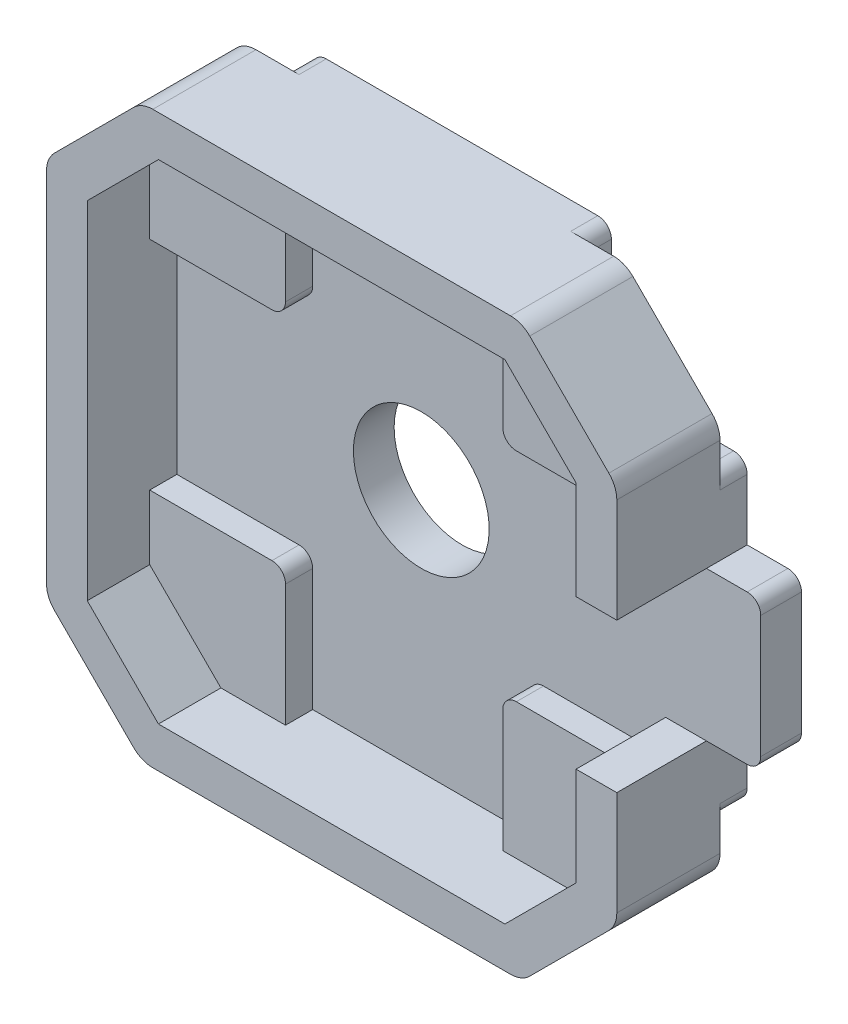
SolidWorks part; units mm, degrees
ref_plane "Front Plane" through (0, 0, 0) normal (0, 0, 1) x (1, 0, 0)
ref_plane "Top Plane" through (0, 0, 0) normal (0, 1, 0) x (1, 0, 0)
ref_plane "Right Plane" through (0, 0, 0) normal (1, 0, 0) x (0, 0, -1)
sketch "Sketch1" plane through (0, 0, 0) normal (0, 0, 1) x (1, 0, 0)
  line L1 (-21, 21) -> (21, 21)
  line L2 (-21, 21) -> (-21, -21)
  line L3 (-21, -21) -> (21, -21)
  line L4 (21, 21) -> (21, -21)
  line L5 (-21, 21) -> (21, -21) construction
  line L6 (-21, -21) -> (21, 21) construction
  point P0 (0, 0)
  dimension "D1" = 42
  dimension "D2" = 42
extrude "Boss-Extrude1" add sketch "Sketch1" along normal mid plane 9.6
sketch "Sketch2" plane through (0, 0, 4.8) normal (0, 0, 1) x (1, 0, 0)
  line L0 (0, 7.5354) -> (0, -7.4639) construction
  line L1 (-9.7138, 0) -> (7.7854, 0) construction
  line L2 (-21, 21) -> (-21, 14)
  line L3 (-21, 21) -> (-21, -21) construction
  line L4 (-21, 14) -> (-14, 21)
  line L5 (21, 21) -> (-21, 21) construction
  line L6 (-14, 21) -> (-21, 21)
  line L7 (14, 21) -> (21, 21)
  line L8 (21, 14) -> (14, 21)
  line L9 (21, 21) -> (21, 14)
  line L10 (21, -21) -> (21, -14)
  line L11 (21, -14) -> (14, -21)
  line L12 (14, -21) -> (21, -21)
  line L13 (-14, -21) -> (-21, -21)
  line L14 (-21, -14) -> (-14, -21)
  line L15 (-21, -21) -> (-21, -14)
  dimension "D1" = 7
  dimension "D2" = 7
extrude "Cut-Extrude1" cut sketch "Sketch2" against normal up to next
sketch "Sketch3" plane through (0, 0, -4.8) normal (0, 0, -1) x (-1, 0, 0)
  line L0 (-21, 11) -> (-11, 11)
  line L1 (-11, 21) -> (-11, 11)
  line L2 (0, 8.821) -> (0, -5.6069) construction
  line L3 (-8.9996, 0) -> (7.5711, 0) construction
  line L4 (-11, 21) -> (11, 21)
  line L5 (-21, 11) -> (-21, -11)
  line L6 (11, 21) -> (11, 11)
  line L7 (21, 11) -> (11, 11)
  line L8 (-14, -21) -> (14, -21)
  line L9 (14, -21) -> (21, -14)
  line L10 (21, -14) -> (21, 14)
  line L11 (21, 14) -> (14, 21)
  line L12 (14, 21) -> (-14, 21)
  line L13 (-14, 21) -> (-21, 14)
  line L14 (-21, 14) -> (-21, -14)
  line L15 (-21, -14) -> (-14, -21)
  line L16 (-14, -21) -> (14, -21) construction
  line L17 (14, -21) -> (21, -14) construction
  line L18 (21, -14) -> (21, 14) construction
  line L19 (21, 14) -> (14, 21) construction
  line L20 (14, 21) -> (-14, 21) construction
  line L21 (-14, 21) -> (-21, 14) construction
  line L22 (-21, 14) -> (-21, -14) construction
  line L23 (-21, -14) -> (-14, -21) construction
  line L24 (21, 11) -> (21, -11)
  line L25 (21, -11) -> (11, -11)
  line L26 (11, -21) -> (11, -11)
  line L27 (-11, -21) -> (11, -21)
  line L28 (-11, -21) -> (-11, -11)
  line L29 (-21, -11) -> (-11, -11)
  point P19 (0, 21)
  point P23 (21, 0)
  point P28 (-21, 0)
  line M23 (-14, -21) -> (14, -21)
  line M24 (14, -21) -> (21, -14)
  line M25 (21, -14) -> (21, 14)
  line M26 (21, 14) -> (14, 21)
  line M27 (14, 21) -> (-14, 21)
  line M28 (-14, 21) -> (-21, 14)
  line M29 (-21, 14) -> (-21, -14)
  line M30 (-21, -14) -> (-14, -21)
  dimension "D2" = 10
  dimension "D3" = 10
  dimension "D1" = 0
extrude "Cut-Extrude2" cut sketch "Sketch3" against normal blind 2 contours L1 L0 M27 M28 M29 | L7 L6 M25 M26 M27 | L26 L25 M23 M24 M25 | L29 L28 M29 M30 M23
sketch "Sketch4" plane through (21, 0, 0) normal (1, 0, 0) x (0, 0, -1)
  line L0 (4.8, -11) -> (4.8, 11) construction
  line L1 (4.8, 5.5) -> (1.8, 5.5)
  line L2 (4.8, 5.5) -> (4.8, -5.5)
  line L3 (4.8, -5.5) -> (1.8, -5.5)
  line L4 (1.8, 5.5) -> (1.8, -5.5)
  dimension "D1" = 11
  dimension "D2" = 3
  dimension "D3" = 5.5
extrude "Boss-Extrude2" add sketch "Sketch4" along normal blind 4
shell "Shell1" thickness 3
sketch "Sketch5" plane through (21, 0, 0) normal (1, 0, 0) x (0, 0, -1)
  line L0 (-4.8, -14) -> (-4.8, 14) construction
  line L1 (1.8, 5.5) -> (-4.8, 5.5)
  line L2 (1.8, 5.5) -> (1.8, -5.5)
  line L3 (1.8, -5.5) -> (-4.8, -5.5)
  line L4 (-4.8, 5.5) -> (-4.8, -5.5)
  line L5 (1.8, -5.5) -> (4.8, -5.5) construction
extrude "Cut-Extrude3" cut sketch "Sketch5" against normal up to next
sketch "Sketch6" plane through (0, 0, -4.8) normal (0, 0, -1) x (-1, 0, 0)
  circle A0 centre (0, 0) radius 5
  dimension "D1" = 10
extrude "Cut-Extrude4" cut sketch "Sketch6" against normal up to next
fillet "Fillet1" radius 2 8 edges at (-14, 21, 1) (-21, 14, 1) (-21, -14, 1) (-14, -21, 1) (14, -21, 1) (21, -14, 1) (21, 14, 1) (14, 21, 1)
fillet "Fillet2" radius 1 14 edges at (25, -5.5, -3.3) (25, 5.5, -3.3) (21, 11, -3.8) (11, 21, -3.8) (-11, 21, -3.8) (-21, 11, -3.8) (-21, -11, -3.8) (-11, -21, -3.8) (11, -21, -3.8) (21, -11, -3.8) (-8, -8, -0.8) (8, -8, -0.8) (-8, 8, -0.8) (8, 8, -0.8)
